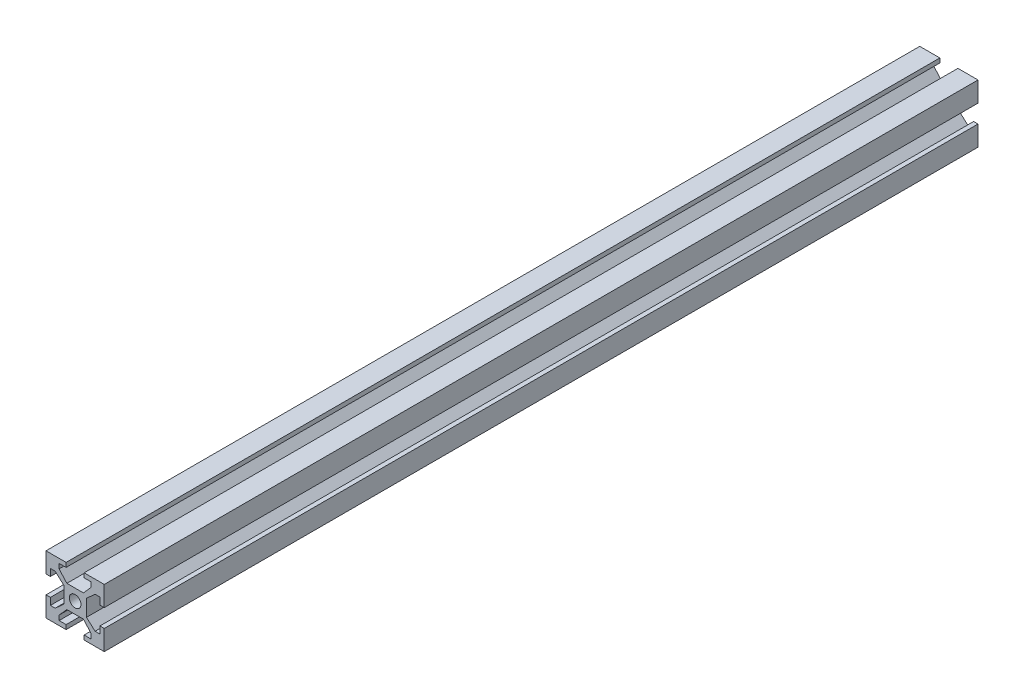
SolidWorks part; units mm, degrees
material "6063-T6"
ref_plane "Front Plane" through (0, 0, 0) normal (0, 0, 1) x (1, 0, 0)
ref_plane "Top Plane" through (0, 0, 0) normal (0, 1, 0) x (1, 0, 0)
ref_plane "Right Plane" through (0, 0, 0) normal (1, 0, 0) x (0, 0, -1)
sketch "Sketch1" plane through (0, 0, 0) normal (0, 0, 1) x (1, 0, 0)
  line L0 (10, 10) -> (4.6104, 10) construction
  line L1 (10, 10) -> (10, 4.6104) construction
  line L2 (10, -10) -> (10, -4.6104) construction
  line L3 (10, -10) -> (4.6104, -10) construction
  line L4 (10, 10) -> (10, 4.6104)
  line L5 (6.8607, 5.5) -> (8.5, 5.5)
  line L6 (5.5, 8.5) -> (5.5, 6.8607)
  line L7 (10, 10) -> (4.6104, 10)
  line L8 (10, 10) -> (10, 4.6104)
  line L9 (6.8607, 5.5) -> (3.9, 2.8393)
  line L10 (5.5, 6.8607) -> (2.8393, 3.9)
  line L13 (8.5, 3.1) -> (8.5, 5.5)
  line L14 (3.1, 8.5) -> (5.5, 8.5)
  line L15 (-6.8607, 5.5) -> (-8.5, 5.5)
  line L16 (6.8607, -5.5) -> (8.5, -5.5)
  line L17 (3.1, -8.5) -> (5.5, -8.5)
  line L18 (8.5, -3.1) -> (8.5, -5.5)
  line L21 (-3.9, 0.5196) -> (-3.9, -0.5196)
  line L22 (-0.5196, 3.9) -> (0.5196, 3.9)
  line L23 (3.9, 0.5196) -> (3.9, -0.5196)
  line L24 (-0.5196, -3.9) -> (0.5196, -3.9)
  line L25 (3.9, 0.5196) -> (3.9, 2.8393)
  line L26 (2.8393, 3.9) -> (0.5196, 3.9)
  line L27 (3.9, -2.8393) -> (3.9, -0.5196)
  line L28 (2.8393, -3.9) -> (0.5196, -3.9)
  line L29 (5.5, -6.8607) -> (2.8393, -3.9)
  line L30 (6.8607, -5.5) -> (3.9, -2.8393)
  line L31 (10, -10) -> (10, -4.6104)
  line L32 (10, -10) -> (4.6104, -10)
  line L33 (5.5, -8.5) -> (5.5, -6.8607)
  line L34 (-6.8607, -5.5) -> (-8.5, -5.5)
  line L35 (10, -10) -> (10, -4.6104)
  line L36 (0, 0) -> (0, 8.5) construction
  line L37 (-10, -10) -> (-4.6104, -10) construction
  line L38 (-10, -10) -> (-10, -4.6104) construction
  line L39 (-10, 10) -> (-10, 4.6104) construction
  line L40 (-10, 10) -> (-4.6104, 10) construction
  line L41 (-10, -10) -> (-10, -4.6104)
  line L42 (-3.1, -8.5) -> (-3.1, -10)
  line L43 (-5.5, -8.5) -> (-5.5, -6.8607)
  line L44 (-10, -10) -> (-4.6104, -10)
  line L45 (-10, -10) -> (-10, -4.6104)
  line L46 (-6.8607, -5.5) -> (-3.9, -2.8393)
  line L47 (-5.5, -6.8607) -> (-2.8393, -3.9)
  line L48 (-2.8393, -3.9) -> (-0.5196, -3.9)
  line L49 (-3.9, -2.8393) -> (-3.9, -0.5196)
  line L50 (-2.8393, 3.9) -> (-0.5196, 3.9)
  line L51 (-3.9, 0.5196) -> (-3.9, 2.8393)
  line L52 (-3.1, -10) -> (-4.6104, -10)
  line L53 (-8.5, -3.1) -> (-10, -3.1)
  line L54 (-10, -3.1) -> (-10, -4.6104)
  line L55 (3.1, -8.5) -> (3.1, -10)
  line L58 (-8.5, -3.1) -> (-8.5, -5.5)
  line L59 (-3.1, -8.5) -> (-5.5, -8.5)
  line L60 (-10, -10) -> (10, -10) construction
  line L61 (-10, -10) -> (-10, 10) construction
  line L62 (-3.1, 8.5) -> (-5.5, 8.5)
  line L63 (-8.5, 3.1) -> (-8.5, 5.5)
  line L66 (-5.5, 6.8607) -> (-2.8393, 3.9)
  line L67 (-6.8607, 5.5) -> (-3.9, 2.8393)
  line L68 (-10, 10) -> (-10, 4.6104)
  line L69 (-10, 10) -> (-4.6104, 10)
  line L70 (-5.5, 8.5) -> (-5.5, 6.8607)
  line L71 (-10, 10) -> (10, 10) construction
  line L72 (-10, 10) -> (-10, 4.6104)
  line L73 (10, -10) -> (10, 10) construction
  line L74 (-10, -10) -> (10, 10) construction
  line L75 (-10, 10) -> (10, -10) construction
  line L76 (3.1, -10) -> (4.6104, -10)
  line L77 (8.5, -3.1) -> (10, -3.1)
  line L78 (10, -3.1) -> (10, -4.6104)
  line L79 (8.5, 3.1) -> (10, 3.1)
  line L80 (10, 3.1) -> (10, 4.6104)
  line L81 (4.6104, 10) -> (3.1, 10)
  line L82 (3.1, 10) -> (3.1, 8.5)
  line L83 (-3.1, 8.5) -> (-3.1, 10)
  line L84 (-3.1, 10) -> (-4.6104, 10)
  line L85 (-8.5, 3.1) -> (-10, 3.1)
  line L86 (-10, 3.1) -> (-10, 4.6104)
  circle A0 centre (0, 0) radius 2
  dimension "D7" = 4
  dimension "D1" = 20
  dimension "D2" = 5.3896
  dimension "D3" = 4.5
  dimension "D5" = 1.5
  dimension "D6" = 1.5104
  dimension "D8" = 5.5
  dimension "D11" = 2.3197
  dimension "D12" = 7.8
  dimension "D13" = 7.8
  dimension "D14" = 1.5
  dimension "D15" = 2.6607
extrude "Boss-Extrude1" add sketch "Sketch1" along normal mid plane 300
